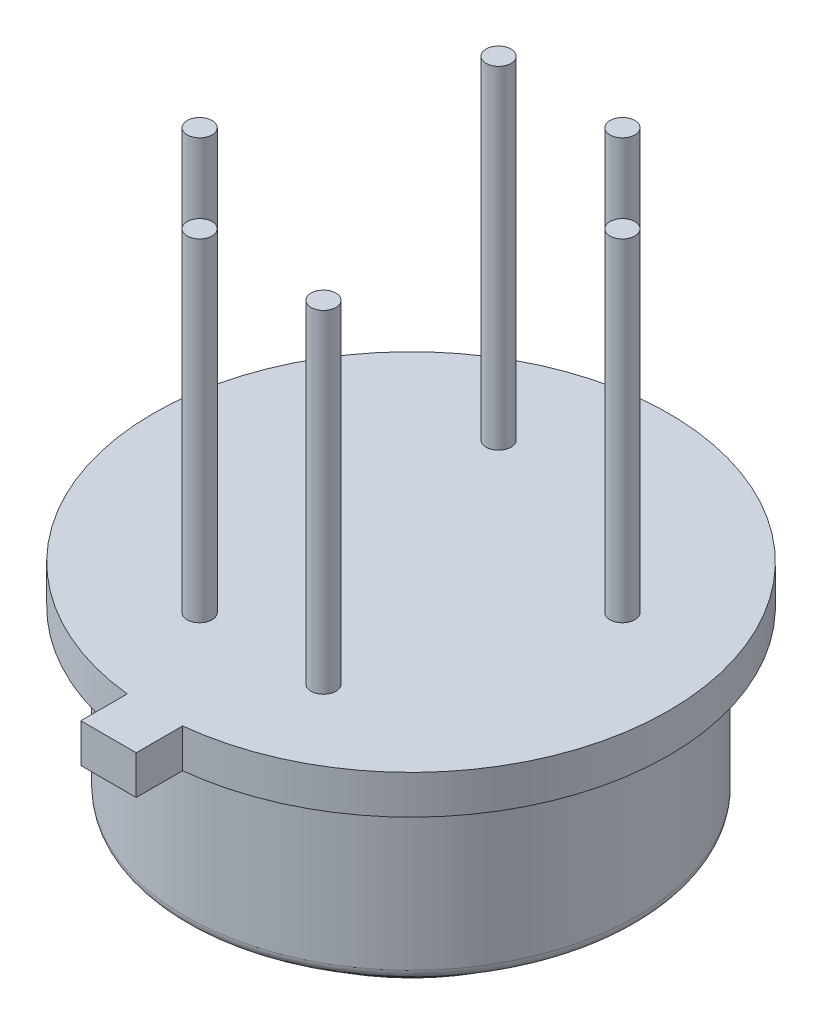
SolidWorks part; units mm, degrees
ref_plane "Front Plane" through (0, 0, 0) normal (0, 0, 1) x (1, 0, 0)
ref_plane "Top Plane" through (0, 0, 0) normal (0, 1, 0) x (1, 0, 0)
ref_plane "Right Plane" through (0, 0, 0) normal (1, 0, 0) x (0, 0, -1)
sketch "Sketch1" plane through (0, 0, 0) normal (0, 1, 0) x (1, 0, 0)
  circle A0 centre (22.6831, -14.2286) radius 4.65
  dimension "D1" = 9.3
extrude "Boss-Extrude1" add sketch "Sketch1" along normal blind 0.7
sketch "Sketch2" plane through (0, 0, 0) normal (0, -1, 0) x (1, 0, 0)
  circle A0 centre (22.6831, 14.2286) radius 4.075
  dimension "D1" = 8.15
extrude "Boss-Extrude2" add sketch "Sketch2" along normal blind 3
sketch "Sketch3" plane through (0, -3, 0) normal (0, -1, 0) x (1, 0, 0)
  circle A0 centre (22.6831, 14.2286) radius 3.25
  dimension "D1" = 6.5
extrude "Boss-Extrude3" add sketch "Sketch3" along normal blind 0.6
fillet "Fillet1" radius 0.2 1 edges at (22.6831, -3, 10.1536)
fillet "Fillet2" radius 0.2 1 edges at (22.6831, -3.6, 10.9786)
sketch "Sketch4" plane through (0, -3.6, 0) normal (0, -1, 0) x (1, 0, 0)
  circle A0 centre (22.6831, 14.2286) radius 1.25
  dimension "D1" = 2.5
extrude "Cut-Extrude1" cut sketch "Sketch4" against normal blind 0.4
sketch "Sketch5" plane through (0, 0.7, 0) normal (0, 1, 0) x (1, 0, 0)
  line L1 (22.1831, -18.0619) -> (23.1831, -18.0619)
  line L2 (22.1831, -18.0619) -> (22.1831, -19.6886)
  line L3 (22.1831, -19.6886) -> (23.1831, -19.6886)
  line L4 (23.1831, -18.0619) -> (23.1831, -19.6886)
  circle A0 centre (22.6831, -14.2286) radius 4.65 construction
  dimension "D1" = 1
  dimension "D2" = 0.5
  dimension "D3" = 5.46
extrude "Boss-Extrude4" add sketch "Sketch5" against normal up to surface (0.7 mm away) up to face at (22.6831, 0, 10.1536)
sketch "Sketch6" plane through (0, 0.7, 0) normal (0, 1, 0) x (1, 0, 0)
  circle A0 centre (19.9854, -15.346) radius 0.225
  circle A1 centre (21.5657, -16.9263) radius 0.225
  circle A2 centre (23.8005, -16.9263) radius 0.225
  circle A3 centre (25.3808, -13.1111) radius 0.225
  circle A4 centre (23.8005, -11.5308) radius 0.225
  circle A5 centre (21.5657, -11.5308) radius 0.225
  dimension "D1" = 0.45
  dimension "D2" = 0.45
  dimension "D3" = 0.45
  dimension "D4" = 0.45
  dimension "D5" = 0.45
  dimension "D6" = 0.45
extrude "Boss-Extrude5" add sketch "Sketch6" along normal blind 6
